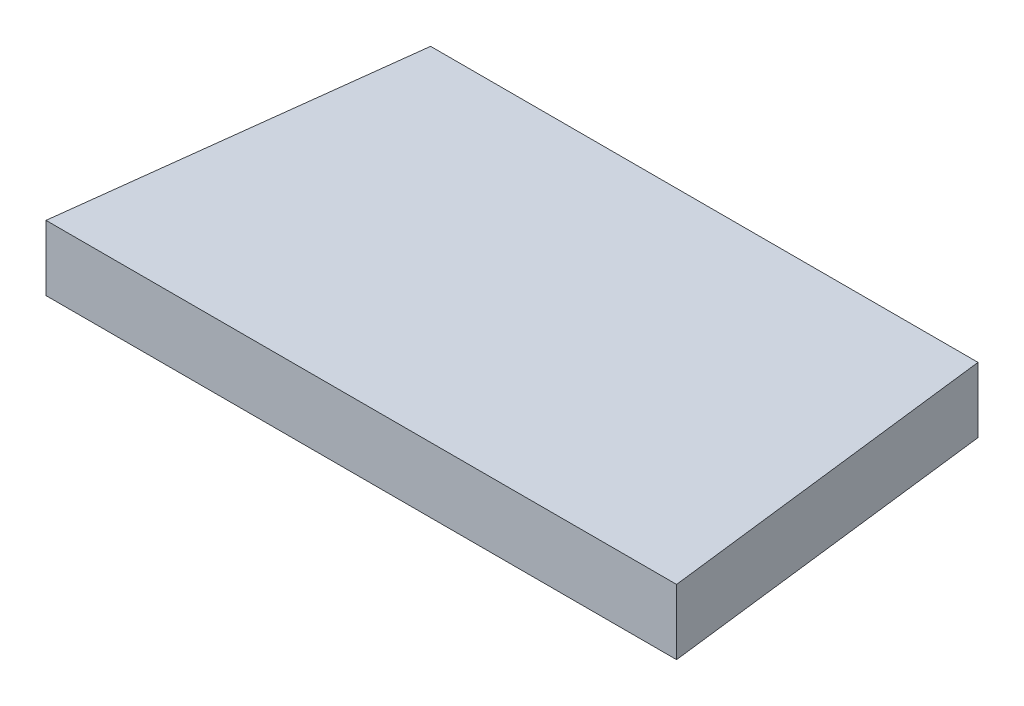
SolidWorks part; units mm, degrees
ref_plane "Front Plane" through (0, 0, 0) normal (0, 0, 1) x (1, 0, 0)
ref_plane "Top Plane" through (0, 0, 0) normal (0, 1, 0) x (1, 0, 0)
ref_plane "Right Plane" through (0, 0, 0) normal (1, 0, 0) x (0, 0, -1)
sketch "Croquis2" plane through (0, 0, 0) normal (0, 1, 0) x (1, 0, 0)
  line L0 (-0.2069, 35.333) -> (-14, 0)
  line L1 (-14, 0) -> (0, 0)
  line L2 (0, 0) -> (4.2931, 35.4086)
  line L3 (4.2931, 35.4086) -> (-0.2069, 35.333)
  line L4 (45.2931, 35.4086) -> (4.2931, 35.4086)
  line L5 (24.7931, 35.4086) -> (24.7931, 17.6731) construction
  line L6 (45.2931, 35.4086) -> (49.7931, 35.333)
  line L7 (49.5861, 0) -> (45.2931, 35.4086)
  line L8 (63.5861, 0) -> (49.5861, 0)
  line L9 (49.7931, 35.333) -> (63.5861, 0)
  line L10 (3.4443, 28.4086) -> (46.1418, 28.4086)
  dimension "D1" = 14
  dimension "D2" = 35.4086
  dimension "D3" = 35.333
  dimension "D4" = 68.676
  dimension "D5" = 4.5
  dimension "D6" = 50
  dimension "D7" = 7
extrude "Saliente-Extruir1" add sketch "Croquis2" along normal blind 30 contours L2 L3 L0 L1 | L5 L4 L2 L10 | L4 L5 L10 L7 | L9 L6 L7 L8
sketch "Croquis4" plane through (0, 0, 0) normal (1, 0, 0) x (0, 0, -1)
  line L0 (0, 0) -> (5, 0)
  line L1 (5, 0) -> (5, 30)
  line L2 (5, 30) -> (-4.9066, 30)
  line L3 (-4.9066, 30) -> (-4.9066, 0)
  line L4 (-4.9066, 0) -> (0, 0)
  dimension "D1" = 9.9066
  dimension "D2" = 5
  dimension "D3" = 30
extrude "Cortar-Extruir2" cut sketch "Croquis4" against normal mid plane 180
sketch "Croquis5" plane through (0, 0, 0) normal (0, -1, 0) x (-1, 0, 0)
  line L0 (-14.7931, 31.4086) -> (-34.7931, 31.4086)
  line L1 (-14.7931, 31.4086) -> (-14.7931, 33.4086)
  line L2 (-34.7931, 31.4086) -> (-34.7931, 33.4086)
  line L3 (-14.7931, 33.4086) -> (-34.7931, 33.4086)
  line L4 (-14.7931, 31.4086) -> (-34.7931, 33.4086) construction
  line L5 (-34.7931, 31.4086) -> (-14.7931, 33.4086) construction
  line L6 (-3.4443, 28.4086) -> (-3.4443, 35.3943) construction
  line L7 (-4.2931, 35.4086) -> (0.2069, 35.333) construction
  line L8 (-3.4443, 28.4086) -> (-46.1418, 28.4086) construction
  line L9 (-45.2931, 35.4086) -> (-4.2931, 35.4086) construction
  point P1 (-24.7931, 32.4086)
  point P12 (-24.7931, 31.4086)
  point P15 (-24.7931, 28.4086)
  dimension "D1" = 2
  dimension "D2" = 20
  dimension "D3" = 2
extrude "Saliente-Extruir2" add sketch "Croquis5" along normal blind 3
chamfer "Chaflán1" distance 15 angle 17 1 edges at (2.0253, 30, -16.7043)
chamfer "Chaflán2" distance 15 angle 17 1 edges at (47.5608, 30, -16.7043)
chamfer "Chaflán3" distance 15 angle 18 1 edges at (24.7931, 30, -28.4086)
sketch "Croquis6" plane through (0, 0, 0) normal (0, -1, 0) x (1, 0, 0)
  line L0 (0.6087, -1.6974) -> (3.7988, -28.0086)
  line L1 (3.7988, -28.0086) -> (45.7873, -28.0086)
  line L2 (45.7873, -28.0086) -> (48.9774, -1.6974)
  line L3 (48.9774, -1.6974) -> (0.6087, -1.6974)
  line L4 (48.9799, -5) -> (46.1418, -28.4086) construction
  line L5 (0.6062, -5) -> (3.4443, -28.4086) construction
  line L6 (3.4443, -28.4086) -> (46.1418, -28.4086) construction
  dimension "D1" = 0.4
  dimension "D2" = 0.4
  dimension "D3" = 0.4
  dimension "D4" = 26.3112
extrude "Saliente-Extruir3" add sketch "Croquis6" against normal blind 5 separate body
sketch "Croquis7" plane through (0, 0, 0) normal (0, -1, 0) x (1, 0, 0)
  line L0 (0.6062, -5) -> (-12.0481, -5)
  line L1 (-12.0481, -5) -> (-0.2069, -35.333)
  line L2 (-0.2069, -35.333) -> (49.7931, -35.333)
  line L3 (49.7931, -35.333) -> (61.6342, -5)
  line L4 (61.6342, -5) -> (48.9799, -5)
  line L5 (48.9799, -5) -> (46.1418, -28.4086)
  line L6 (46.1418, -28.4086) -> (3.4443, -28.4086)
  line L7 (3.4443, -28.4086) -> (0.6062, -5)
  line L8 (-0.2069, -35.333) -> (0.6062, -38.3065)
  line L9 (0.6062, -38.3065) -> (49.7931, -38.3065)
  line L10 (49.7931, -38.3065) -> (49.7931, -35.333)
  line M9 (49.7931, -35.333) -> (61.6342, -5)
  line M10 (61.6342, -5) -> (48.9799, -5)
  line M11 (48.9799, -5) -> (46.1418, -28.4086)
  line M12 (46.1418, -28.4086) -> (3.4443, -28.4086)
  line M13 (3.4443, -28.4086) -> (0.6062, -5)
  line M14 (0.6062, -5) -> (-12.0481, -5)
  line M15 (-12.0481, -5) -> (-0.2069, -35.333)
  line M16 (-0.2069, -35.333) -> (4.2931, -35.4086)
  line M17 (4.2931, -35.4086) -> (45.2931, -35.4086)
  line M18 (45.2931, -35.4086) -> (49.7931, -35.333)
  line M19 (14.7931, -33.4086) -> (14.7931, -31.4086)
  line M20 (14.7931, -31.4086) -> (34.7931, -31.4086)
  line M21 (34.7931, -31.4086) -> (34.7931, -33.4086)
  line M22 (34.7931, -33.4086) -> (14.7931, -33.4086)
extrude "Cortar-Extruir3" cut sketch "Croquis7" against normal blind 65 contours L9 L10 L8 M18 M17 M16 | L2 M15 M9 M10 M11 M12 M13 M14 M22 M19 M20 M21 | M19 M22 M21 M20
sketch "Croquis8" plane through (0, 0, -35.4086) normal (0, 0, -1) x (-1, 0, 0)
  line L0 (5.8516, -21.1526) -> (-63.227, -21.1526)
  line L1 (-63.227, -21.1526) -> (-63.227, 42.0925)
  line L2 (-63.227, 42.0925) -> (5.8516, 42.0925)
  line L3 (5.8516, 42.0925) -> (5.8516, -21.1526)
extrude "Cortar-Extruir4" cut sketch "Croquis8" against normal blind 5
